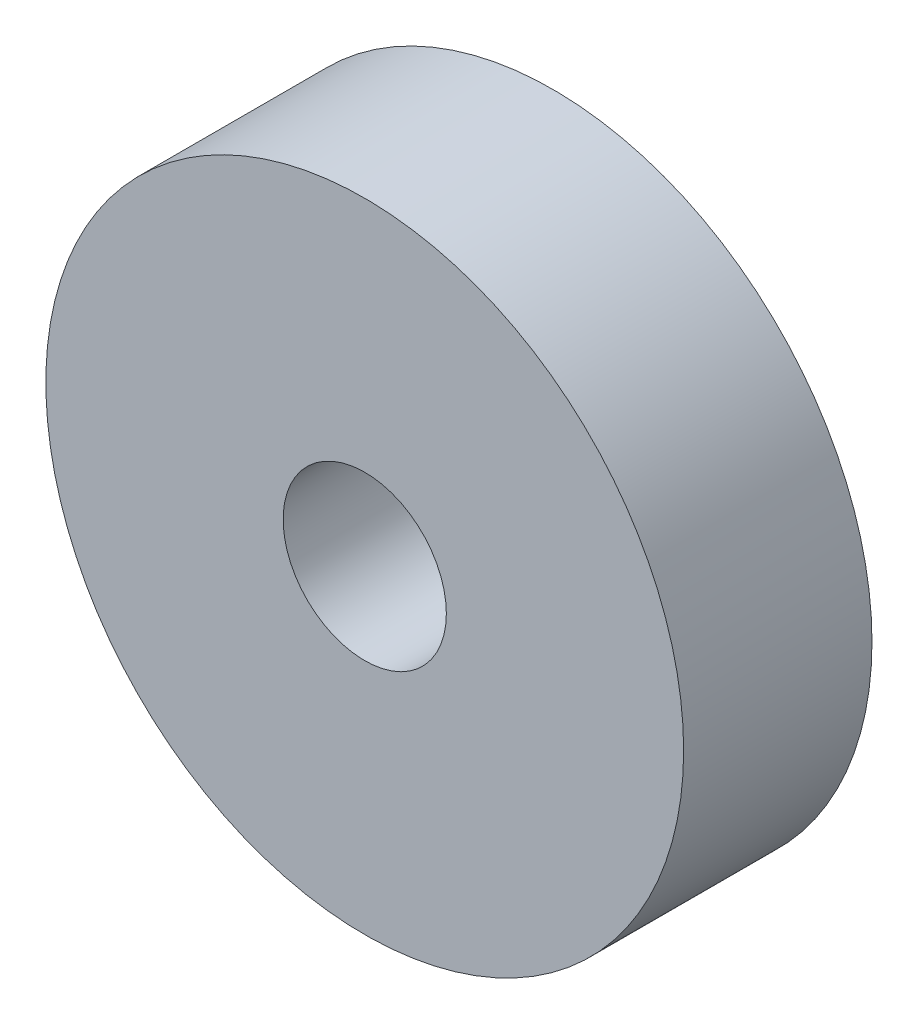
SolidWorks part; units mm, degrees
ref_plane "Front Plane" through (0, 0, 0) normal (0, 0, 1) x (1, 0, 0)
ref_plane "Top Plane" through (0, 0, 0) normal (0, 1, 0) x (1, 0, 0)
ref_plane "Right Plane" through (0, 0, 0) normal (1, 0, 0) x (0, 0, -1)
sketch "Sketch1" plane through (0, 0, 0) normal (0, 0, 1) x (1, 0, 0)
  circle A0 centre (0, 0) radius 1.3
  circle A1 centre (0, 0) radius 5.08
  dimension "D1" = 2.6
  dimension "D2" = 10.16
extrude "Boss-Extrude1" add sketch "Sketch1" along normal blind 3
